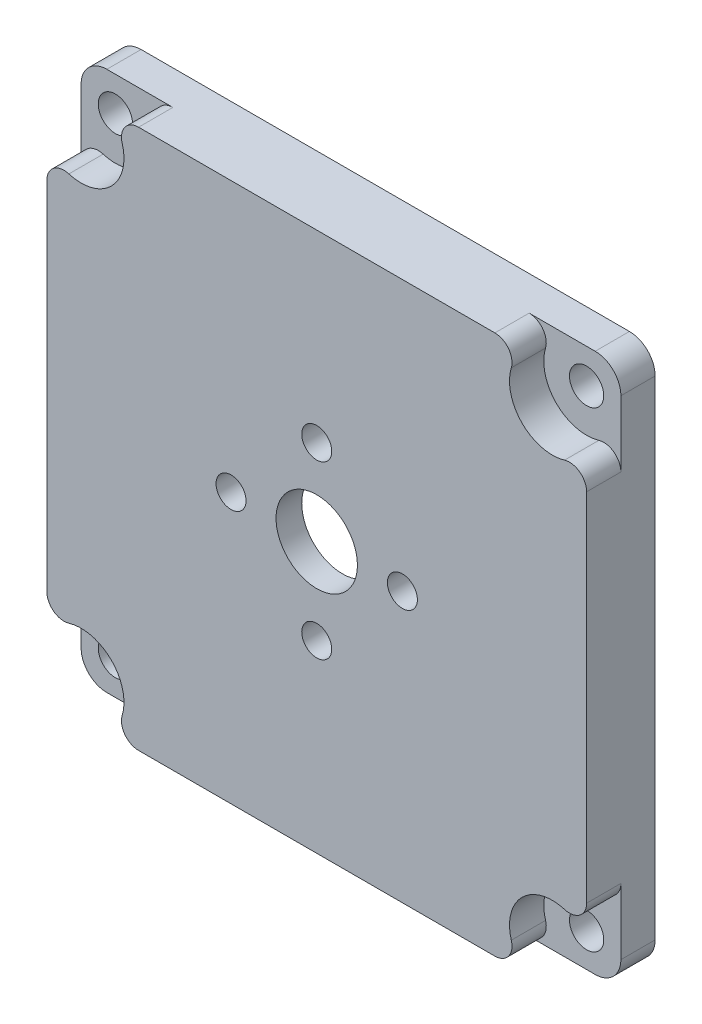
SolidWorks part; units mm, degrees
ref_plane "Front Plane" through (0, 0, 0) normal (0, 0, 1) x (1, 0, 0)
ref_plane "Top Plane" through (0, 0, 0) normal (0, 1, 0) x (1, 0, 0)
ref_plane "Right Plane" through (0, 0, 0) normal (1, 0, 0) x (0, 0, -1)
sketch "Sketch1" plane through (0, 0, 0) normal (0, 0, 1) x (1, 0, 0)
  line L1 (31.5, -31.5) -> (-31.5, -31.5)
  line L2 (31.5, -31.5) -> (31.5, 31.5)
  line L3 (31.5, 31.5) -> (-31.5, 31.5)
  line L4 (-31.5, -31.5) -> (-31.5, 31.5)
  line L5 (31.5, -31.5) -> (-31.5, 31.5) construction
  line L6 (31.5, 31.5) -> (-31.5, -31.5) construction
  point P0 (0, 0)
  dimension "D1" = 63
  dimension "D2" = 63
extrude "Boss-Extrude1" add sketch "Sketch1" along normal blind 8
ref_plane "Plane1" through (0, 0, 0) normal (0, 0, -1) x (-1, 0, 0)
sketch "Sketch2" plane through (0, 0, 0) normal (0, 0, -1) x (-1, 0, 0)
  line L1 (22.5, -22.5) -> (-22.5, -22.5)
  line L2 (22.5, -22.5) -> (22.5, 22.5)
  line L3 (22.5, 22.5) -> (-22.5, 22.5)
  line L4 (-22.5, -22.5) -> (-22.5, 22.5)
  line L5 (22.5, -22.5) -> (-22.5, 22.5) construction
  line L6 (22.5, 22.5) -> (-22.5, -22.5) construction
  point P0 (0, 0)
  dimension "D1" = 45
  dimension "D2" = 45
extrude "Cut-Extrude1" cut sketch "Sketch2" against normal blind 5
ref_plane "Plane2" through (0, 0, 8) normal (0, 0, 1) x (1, 0, 0)
sketch "Sketch3" plane through (0, 0, 8) normal (0, 0, 1) x (1, 0, 0)
  circle A0 centre (0, 0) radius 4.75
  dimension "D1" = 9.5
extrude "Cut-Extrude2" cut sketch "Sketch3" against normal blind 5
sketch "Sketch4" plane through (0, 0, 8) normal (0, 0, 1) x (1, 0, 0)
  line L0 (0, 23.6606) -> (0, -26.5638) construction
  circle A0 centre (0, 10) radius 1.75
  dimension "D1" = 3.5
  dimension "D2" = 10
extrude "Cut-Extrude3" cut sketch "Sketch4" against normal blind 5
pattern_circular "CirPattern1" count 4 over 360 about axis through (0, 0, 0) along (0, 0, 1) of "Cut-Extrude3"
sketch "Sketch5" plane through (0, 0, 8) normal (0, 0, 1) x (1, 0, 0)
  circle A0 centre (-27.5, 27.5) radius 2
  dimension "D1" = 4
  dimension "D2" = 27.5
  dimension "D3" = 27.5
extrude "Cut-Extrude4" cut sketch "Sketch5" against normal blind 15
pattern_circular "CirPattern2" count 4 over 360 about axis through (0, 0, 0) along (0, 0, 1) of "Cut-Extrude4"
fillet "Fillet1" radius 3 4 edges at (-31.5, -31.5, 4) (31.5, -31.5, 4) (31.5, 31.5, 4) (-31.5, 31.5, 4)
sketch "Sketch6" plane through (0, 0, 8) normal (0, 0, 1) x (1, 0, 0)
  circle A0 centre (-27.5, 27.5) radius 5
  dimension "D1" = 10
extrude "Cut-Extrude5" cut sketch "Sketch6" against normal blind 4
pattern_circular "CirPattern3" count 4 over 360 about axis through (0, 0, 0) along (0, 0, 1) of "Cut-Extrude5"
fillet "Fillet2" radius 2 8 edges at (-24.5, -31.5, 6) (-31.5, -24.5, 6) (24.5, -31.5, 6) (31.5, -24.5, 6) (31.5, 24.5, 6) (24.5, 31.5, 6) (-31.5, 24.5, 6) (-24.5, 31.5, 6)
fillet "Fillet3" radius 2 4 edges at (-22.5, -22.5, 2.5) (22.5, -22.5, 2.5) (-22.5, 22.5, 2.5) (22.5, 22.5, 2.5)
